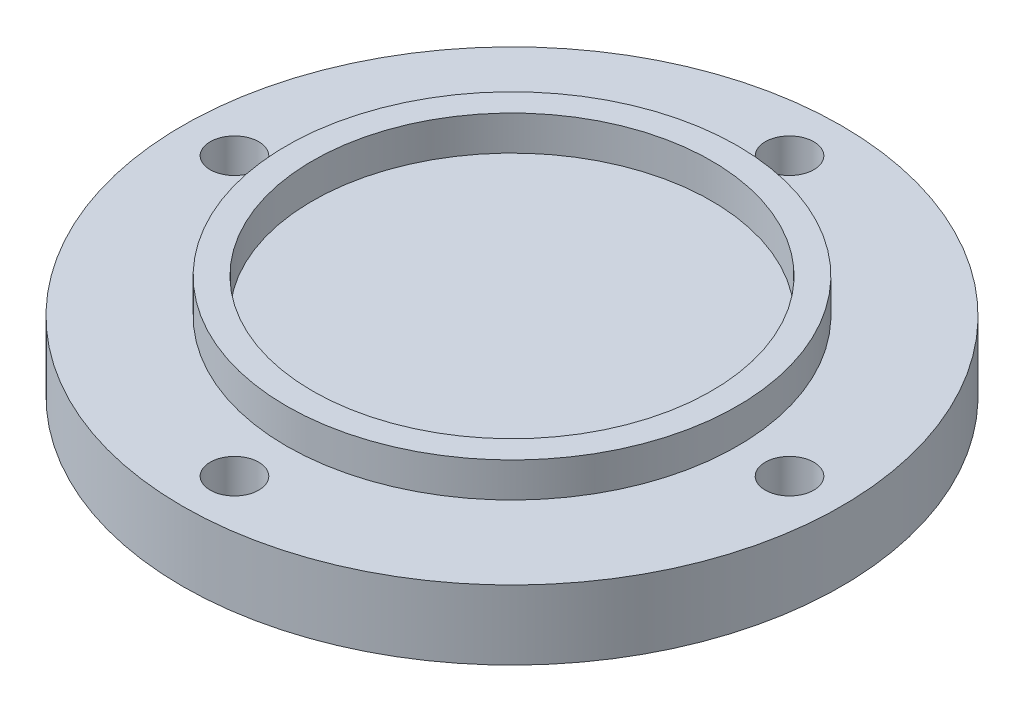
SolidWorks part; units mm, degrees
ref_plane "Front Plane" through (0, 0, 0) normal (0, 0, 1) x (1, 0, 0)
ref_plane "Top Plane" through (0, 0, 0) normal (0, 1, 0) x (1, 0, 0)
ref_plane "Right Plane" through (0, 0, 0) normal (1, 0, 0) x (0, 0, -1)
sketch "Sketch1" plane through (0, 0, 0) normal (0, 1, 0) x (1, 0, 0)
  circle A0 centre (0, 0) radius 95
  dimension "D1" = 190
extrude "Boss-Extrude1" add sketch "Sketch1" along normal mid plane 20 contours A0
sketch "Sketch2" plane through (0, 10, 0) normal (0, 1, 0) x (1, 0, 0)
  circle A0 centre (0, 0) radius 65
  dimension "D1" = 130
extrude "Boss-Extrude2" add sketch "Sketch2" along normal blind 10
sketch "Sketch3" plane through (0, 20, 0) normal (0, 1, 0) x (1, 0, 0)
  circle A0 centre (0, 0) radius 57.5
  dimension "D1" = 115
extrude "Cut-Extrude1" cut sketch "Sketch3" against normal blind 10
sketch "Sketch4" plane through (0, 10, 0) normal (0, 1, 0) x (1, 0, 0)
  line L0 (0, -105.345) -> (0, 103.136) construction
  circle A0 centre (0, 80) radius 7
  circle A1 centre (80, 0) radius 7
  circle A2 centre (0, -80) radius 7
  circle A3 centre (-80, 0) radius 7
  point P15 (0, 0)
  dimension "D2" = 14
  dimension "D1" = 80
  dimension "D3" = 4
extrude "Cut-Extrude2" cut sketch "Sketch4" against normal through all
